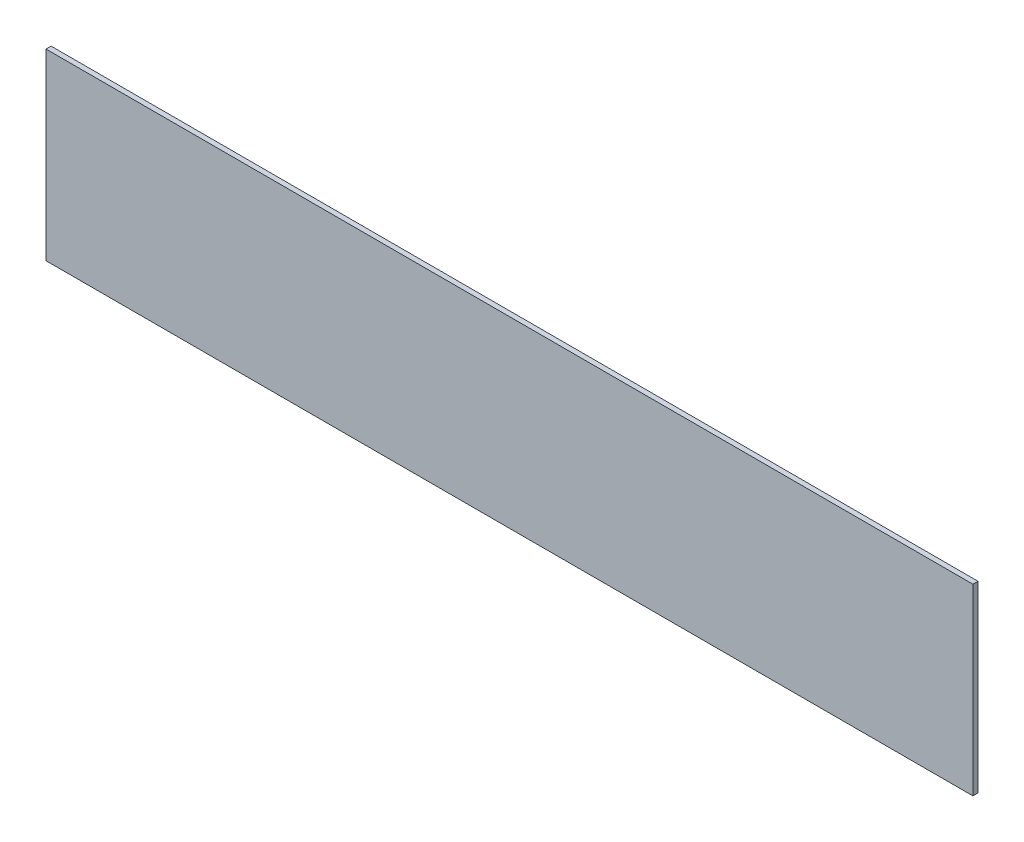
SolidWorks part; units mm, degrees
ref_plane "Front Plane" through (0, 0, 0) normal (0, 0, 1) x (1, 0, 0)
ref_plane "Top Plane" through (0, 0, 0) normal (0, 1, 0) x (1, 0, 0)
ref_plane "Right Plane" through (0, 0, 0) normal (1, 0, 0) x (0, 0, -1)
other "Configuration Table"
sketch "Sketch1" plane through (0, 0, 0) normal (0, 0, 1) x (1, 0, 0)
  line L1 (259, 1737) -> (441, 1737)
  line L2 (259, 1737) -> (259, 1773)
  line L3 (259, 1773) -> (441, 1773)
  line L4 (441, 1737) -> (441, 1773)
extrude "TOPPING_klape_kat1_kulp_cukuru_1" add sketch "Sketch1" along normal blind 1 from offset 26 separate body
